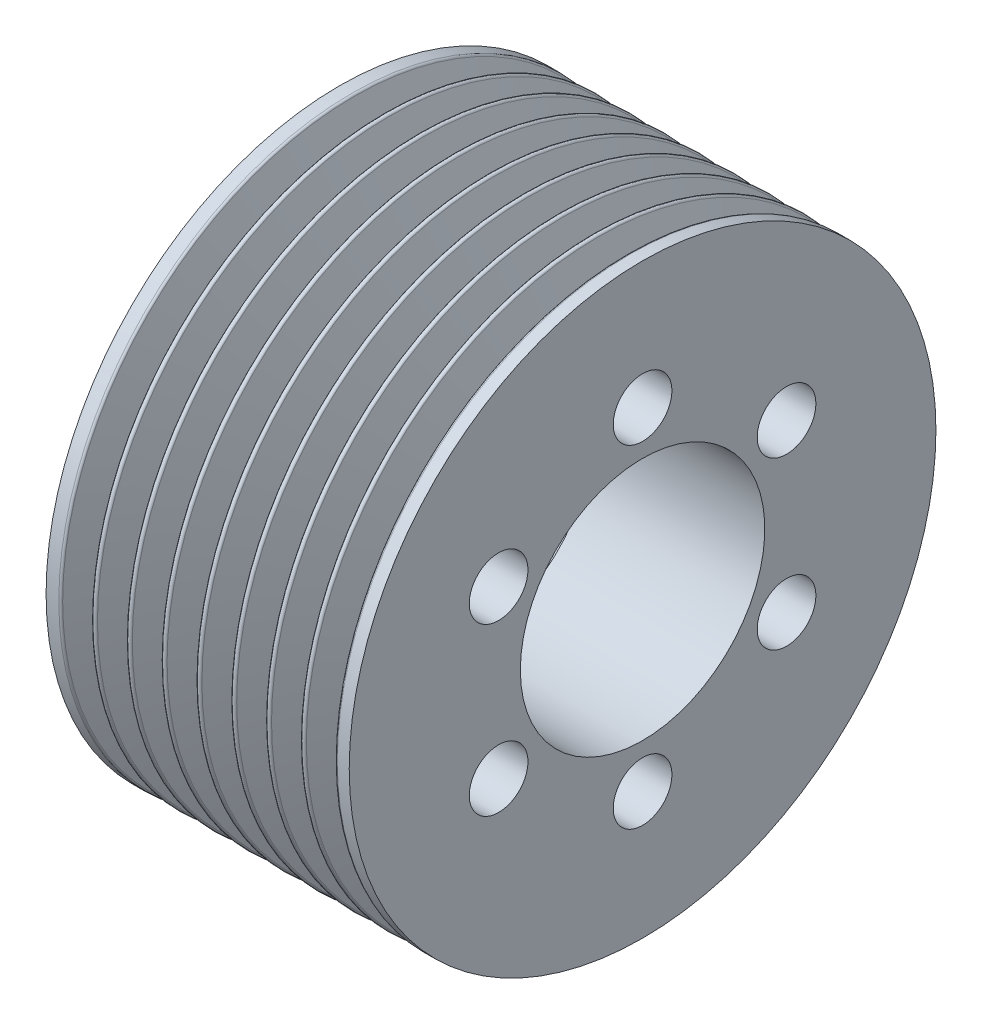
SolidWorks part; units mm, degrees
material "2018 Alloy"
ref_plane "Front Plane" through (0, 0, 0) normal (0, 0, 1) x (1, 0, 0)
ref_plane "Top Plane" through (0, 0, 0) normal (0, 1, 0) x (1, 0, 0)
ref_plane "Right Plane" through (0, 0, 0) normal (1, 0, 0) x (0, 0, -1)
sketch "Sketch1" plane through (0, 0, 0) normal (0, 0, 1) x (1, 0, 0)
  line L0 (49, 12.5) -> (49, 0) construction
  line L1 (49, 12.5) -> (49, 30)
  line L2 (49, 30) -> (18, 30)
  line L3 (18, 30) -> (18, 21.5)
  line L4 (49, 12.5) -> (31.5, 12.5)
  line L5 (0, 0) -> (49, 0) construction
  line L6 (18, 21.5) -> (31.5, 21.5)
  line L8 (0, 8.3175) -> (0, 0) construction
  line L9 (31.5, 12.5) -> (31.5, 21.5)
  dimension "D1" = 31
  dimension "D2" = 60
  dimension "D3" = 31.5
  dimension "D4" = 43
  dimension "D5" = 49
  dimension "D8" = 25
revolve "Revolve1" add sketch "Sketch1" angle 360 about L5
sketch "Sketch2" plane through (0, 0, 0) normal (0, 0, 1) x (1, 0, 0)
  line L0 (47.5458, 29.8376) -> (46.281, 26.4546)
  line L1 (45.719, 26.4546) -> (44.4542, 29.8376)
  line L2 (47.5458, 29.8376) -> (47.6066, 30) construction
  line L3 (49, 30) -> (18, 30) construction
  line L4 (44.4542, 29.8376) -> (44.3934, 30) construction
  line L5 (49, -30) -> (49, 30) construction
  line L6 (47.78, 30) -> (44.22, 30)
  line L7 (0, 0) -> (49, 0) construction
  arc A0 (47.5458, 29.8376) -> (47.78, 30) centre (47.78, 29.75) cw
  arc A1 (44.4542, 29.8376) -> (44.22, 30) centre (44.22, 29.75) ccw
  arc A2 (46.281, 26.4546) -> (45.719, 26.4546) centre (46, 26.5597) cw
  dimension "D2" = 0.25
  dimension "D3" = 0.3
  dimension "D1" = 41
  dimension "D4" = 3.56
  dimension "D5" = 3
revolve "Cut-Revolve1" cut sketch "Sketch2" angle 360 about L7
pattern_linear "LPattern1" count 8 spacing 3.56 along (-1, 0, 0) of "Cut-Revolve1"
sketch "Sketch3" plane through (49, 0, 0) normal (1, 0, 0) x (0, 0, -1)
  circle A0 centre (0, 0) radius 17 construction
  circle A1 centre (0, 17) radius 3
  circle A2 centre (14.7224, 8.5) radius 3
  circle A3 centre (14.7224, -8.5) radius 3
  circle A4 centre (0, -17) radius 3
  circle A5 centre (-14.7224, -8.5) radius 3
  circle A6 centre (-14.7224, 8.5) radius 3
  dimension "D1" = 34
  dimension "D2" = 6
  dimension "D3" = 6
extrude "Cut-Extrude1" cut sketch "Sketch3" against normal up to surface (17.5 mm away) up to face at (31.5, 0, 12.5)
